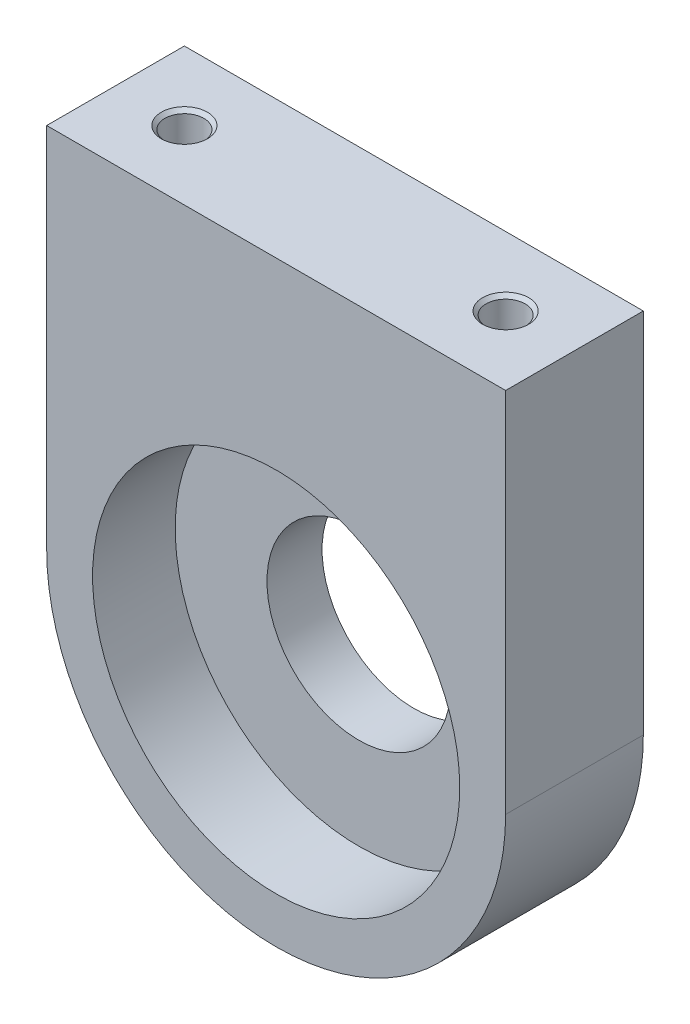
SolidWorks part; units mm, degrees
ref_plane "Front Plane" through (0, 0, 0) normal (0, 0, 1) x (1, 0, 0)
ref_plane "Top Plane" through (0, 0, 0) normal (0, 1, 0) x (1, 0, 0)
ref_plane "Right Plane" through (0, 0, 0) normal (1, 0, 0) x (0, 0, -1)
sketch "Sketch2" plane through (0, 0, 0) normal (0, 0, 1) x (1, 0, 0)
  line L0 (-50, 0) -> (-50, 80)
  line L1 (55, 0) -> (-55, 0) construction
  line L2 (-50, 80) -> (50, 80)
  line L3 (50, 80) -> (50, 0)
  arc A0 (-50, 0) -> (50, 0) centre (0, 0) ccw
  dimension "D4" = 50
  dimension "D1" = 80
  dimension "D2" = 100
  dimension "D3" = 50
extrude "Boss-Extrude1" add sketch "Sketch2" along normal mid plane 30
sketch "Sketch3" plane through (0, 80, 0) normal (0, 1, 0) x (1, 0, 0)
  line L0 (-55, 0) -> (55, 0) construction
  line L1 (0, -16.5) -> (0, 16.5) construction
  point P0 (-35, 0)
  point P1 (35, 0)
  dimension "D1" = 70
  dimension "D2" = 35
sketch "Sketch4" plane through (0, 0, 15) normal (0, 0, 1) x (1, 0, 0)
  circle A0 centre (0, 0) radius 20
  dimension "D1" = 40
extrude "Cut-Extrude1" cut sketch "Sketch4" against normal blind 30
sketch "Sketch5" plane through (0, 0, 15) normal (0, 0, 1) x (1, 0, 0)
  circle A0 centre (0, 0) radius 40
  dimension "D1" = 80
extrude "Cut-Extrude2" cut sketch "Sketch5" against normal blind 18
hole_wizard "M10 Tapped Hole1" positions "3DSketch2" profile "Sketch7" tap size "M10" standard "ISO"
sketch3d "3DSketch2"
  point P0 (-35, 80, 0)
  point P3 (35, 80, 0)
sketch "Sketch7" plane through (-35, 80, 0) normal (1, 0, 0) x (0, 0, 1)
  line L0 (0, 0) -> (0, 27.0537)
  line L1 (0, 27.0537) -> (4.25, 24.5)
  line L2 (4.25, 24.5) -> (4.25, 0.775)
  line L3 (4.25, 0.775) -> (5.025, 0)
  line L5 (5.025, 0) -> (0, 0)
  line L6 (-4.25, 0.775) -> (-5.025, 0) construction
  line L10 (0, 27.0537) -> (-4.25, 24.5) construction
  line L11 (0, -6.35) -> (0, 107.95) construction
  dimension "Tap Drill Dia." = 8.5
  dimension "Tap Drill Depth" = 24.5
  dimension "Near C'Sink Dia." = 10.05
  dimension "Near C'Sink Angle" = 90
  dimension "Drill Angle" = 118
